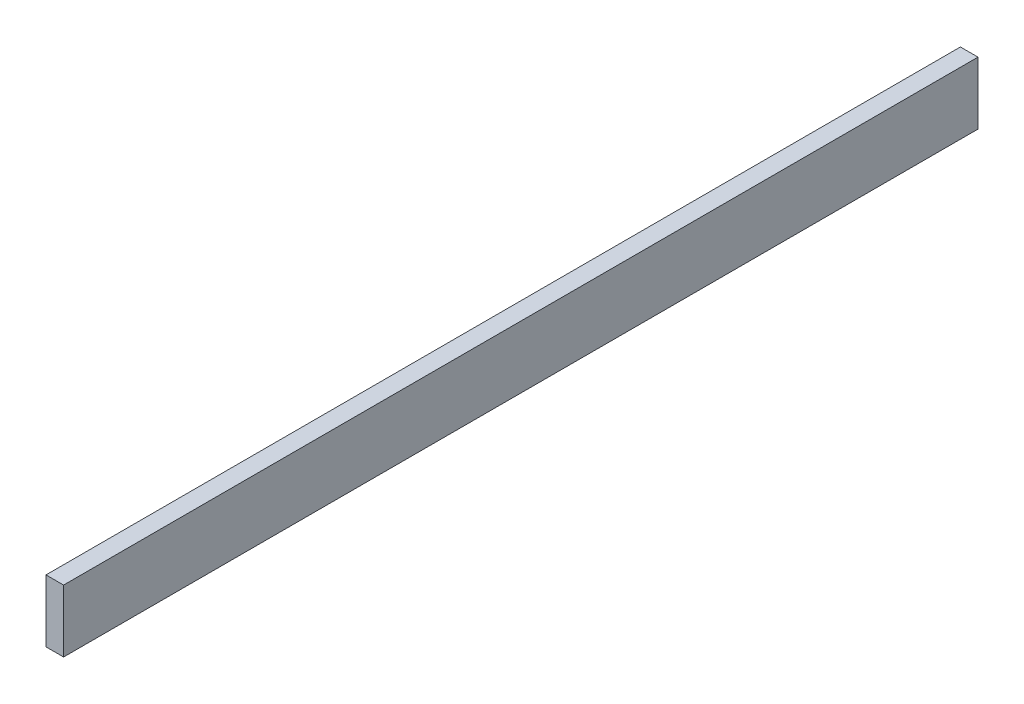
SolidWorks part; units mm, degrees
ref_plane "Front Plane" through (0, 0, 0) normal (0, 0, 1) x (1, 0, 0)
ref_plane "Top Plane" through (0, 0, 0) normal (0, 1, 0) x (1, 0, 0)
ref_plane "Right Plane" through (0, 0, 0) normal (1, 0, 0) x (0, 0, -1)
other "Configuration Table"
sketch "Sketch1" plane through (0, 0, 0) normal (0, 0, 1) x (1, 0, 0)
  line L1 (605.3, 18) -> (618, 18)
  line L2 (605.3, 18) -> (605.3, 63)
  line L3 (605.3, 63) -> (618, 63)
  line L4 (618, 18) -> (618, 63)
extrude "CEK_donmus_ray_ic_profil_sag_1" add sketch "Sketch1" against normal blind 660 separate body
